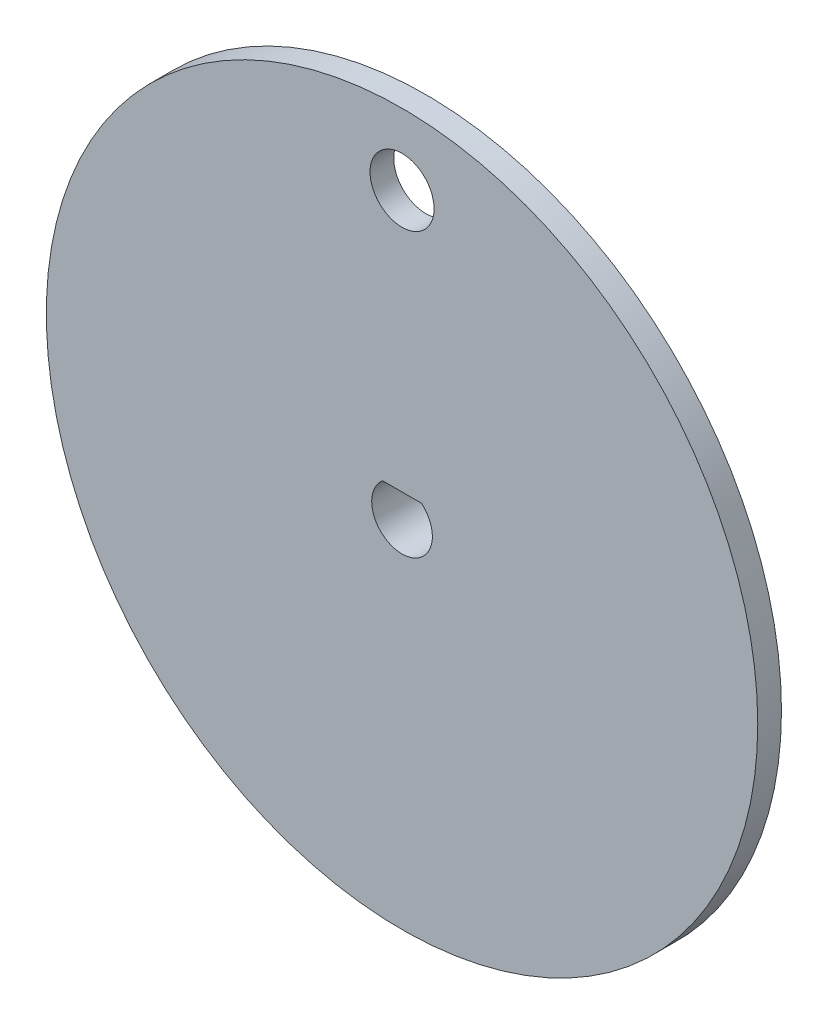
SolidWorks part; units mm, degrees
ref_plane "Front Plane" through (0, 0, 0) normal (0, 0, 1) x (1, 0, 0)
ref_plane "Top Plane" through (0, 0, 0) normal (0, 1, 0) x (1, 0, 0)
ref_plane "Right Plane" through (0, 0, 0) normal (1, 0, 0) x (0, 0, -1)
sketch "Sketch1" plane through (0, 0, 0) normal (0, 0, 1) x (1, 0, 0)
  circle A0 centre (0, 0) radius 38.1
  dimension "D1" = 76.2
extrude "Boss-Extrude1" add sketch "Sketch1" along normal blind 2.54
sketch "Sketch2" plane through (0, 0, 2.54) normal (0, 0, 1) x (1, 0, 0)
  line L0 (0, 38.1) -> (0, -38.1) construction
  circle A0 centre (0, 0) radius 38.1 construction
  circle A2 centre (0, 30.48) radius 3.429
  dimension "D1" = 6.858
  dimension "D2" = 30.48
sketch "Sketch3" plane through (0, 0, 0) normal (0, 0, -1) x (-1, 0, 0)
  circle A0 centre (0, 0) radius 6.35
  dimension "D1" = 12.7
extrude "Boss-Extrude3" add sketch "Sketch3" along normal blind 19.05
extrude "Cut-Extrude1" cut sketch "Sketch2" against normal through all contours A2
sketch "Sketch4" plane through (0, 0, -19.05) normal (0, 0, -1) x (-1, 0, 0)
  line L0 (-2.0767, 2.5) -> (2.0767, 2.5)
  arc A0 (-2.0767, 2.5) -> (2.0767, 2.5) centre (0, 0) ccw
  point P1 (0, -3.25)
  dimension "D1" = 6.5
  dimension "D2" = 5.75
extrude "Cut-Extrude2" cut sketch "Sketch4" against normal through all
